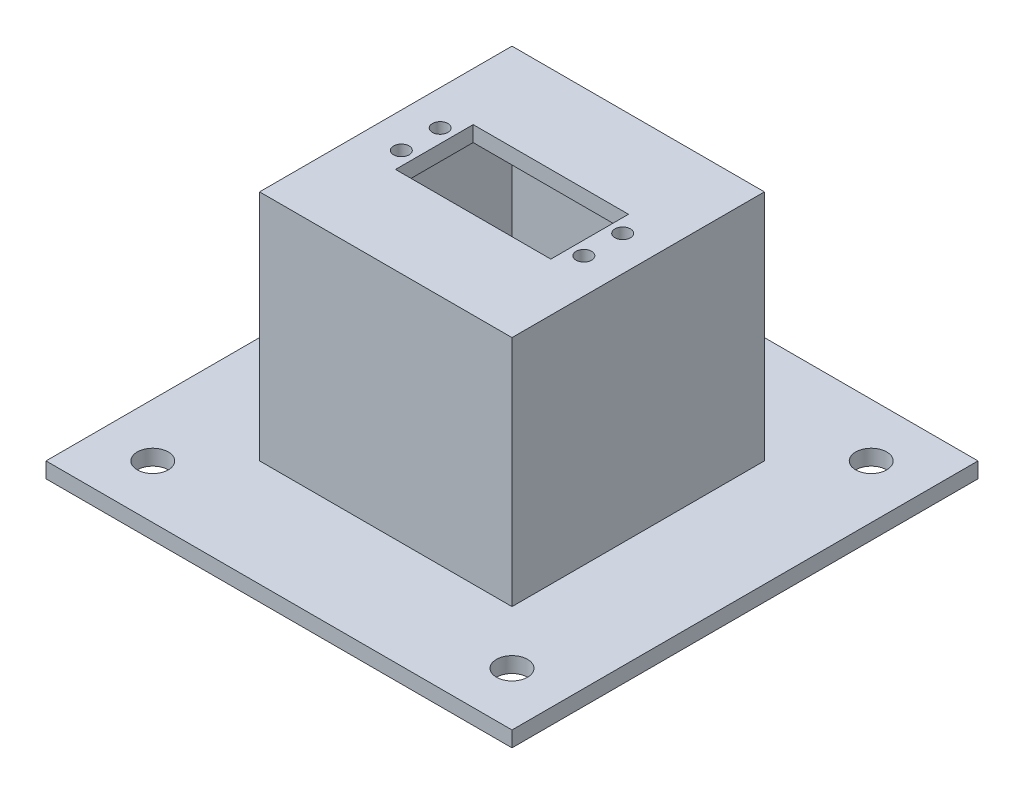
SolidWorks part; units mm, degrees
ref_plane "Ön Düzlem" through (0, 0, 0) normal (0, 0, 1) x (1, 0, 0)
ref_plane "Üst Düzlem" through (0, 0, 0) normal (0, 1, 0) x (1, 0, 0)
ref_plane "Sağ Düzlem" through (0, 0, 0) normal (1, 0, 0) x (0, 0, -1)
sketch "Çizim1" plane through (0, 0, 0) normal (0, 1, 0) x (1, 0, 0)
  line L1 (0, 0) -> (-65, 0)
  line L2 (0, 0) -> (0, 65)
  line L3 (0, 65) -> (-65, 65)
  line L4 (-65, 0) -> (-65, 65)
  dimension "D1" = 65
  dimension "D2" = 65
extrude "Yükseklik-Ekstrüzyon1" add sketch "Çizim1" along normal blind 60
shell "İç Boşaltma1" thickness 4
sketch "Çizim10" plane through (0, 0, 0) normal (0, -1, 0) x (1, 0, 0)
  line L1 (0, -65) -> (-65, -65)
  line L2 (0, -65) -> (0, 0)
  line L3 (0, 0) -> (-65, 0)
  line L4 (-65, -65) -> (-65, 0)
  line L5 (27.5, -92.5) -> (-92.5, -92.5)
  line L6 (27.5, -92.5) -> (27.5, 27.5)
  line L7 (27.5, 27.5) -> (-92.5, 27.5)
  line L8 (-92.5, -92.5) -> (-92.5, 27.5)
  dimension "D1" = 120
  dimension "D2" = 120
  dimension "D3" = 27.5
  dimension "D4" = 27.5
extrude "Yükseklik-Ekstrüzyon5" add sketch "Çizim10" along normal blind 4 separate body
sketch "Çizim11" plane through (0, 0, 0) normal (0, 1, 0) x (1, 0, 0)
  line L0 (-65, 65) -> (-92.5, 92.5) construction
  line L1 (-32.5, 65) -> (-32.5, 92.5) construction
  line L2 (-65, 65) -> (0, 65) construction
  line L3 (-92.5, 92.5) -> (27.5, 92.5) construction
  line L4 (-65, 32.5) -> (-75.417, 32.5) construction
  line L5 (-65, 65) -> (-65, 0) construction
  circle A0 centre (-78.75, 78.75) radius 4
  circle A1 centre (-78.75, -13.75) radius 4
  circle A2 centre (13.75, -13.75) radius 4
  circle A3 centre (13.75, 78.75) radius 4
  dimension "D1" = 8
extrude "Kes-Ekstrüzyon4" cut sketch "Çizim11" against normal up to next (4 mm away)
sketch "Çizim12" plane through (0, 60, 0) normal (0, 1, 0) x (1, 0, 0)
  line L0 (-65, 65) -> (-65, 0) construction
  line L1 (-12.5, 22.5) -> (-52.5, 22.5)
  line L2 (-12.5, 22.5) -> (-12.5, 42.5)
  line L3 (-12.5, 42.5) -> (-52.5, 42.5)
  line L4 (-52.5, 22.5) -> (-52.5, 42.5)
  line L5 (-65, 65) -> (0, 65) construction
  line L7 (-52.5, 32.5) -> (-56, 32.5) construction
  line L8 (-56, 32.5) -> (-56, 37.5) construction
  line L9 (-32.5, 22.5) -> (-32.5, 28.3804) construction
  circle A0 centre (-56, 37.5) radius 2
  circle A1 centre (-56, 27.5) radius 2
  circle A2 centre (-9, 27.5) radius 2
  circle A3 centre (-9, 37.5) radius 2
  dimension "D7" = 4
  dimension "D1" = 40
  dimension "D2" = 20
  dimension "D3" = 12.5
  dimension "D4" = 22.5
  dimension "D5" = 3.5
  dimension "D6" = 5
extrude "Kes-Ekstrüzyon5" cut sketch "Çizim12" against normal up to next (4 mm away)
